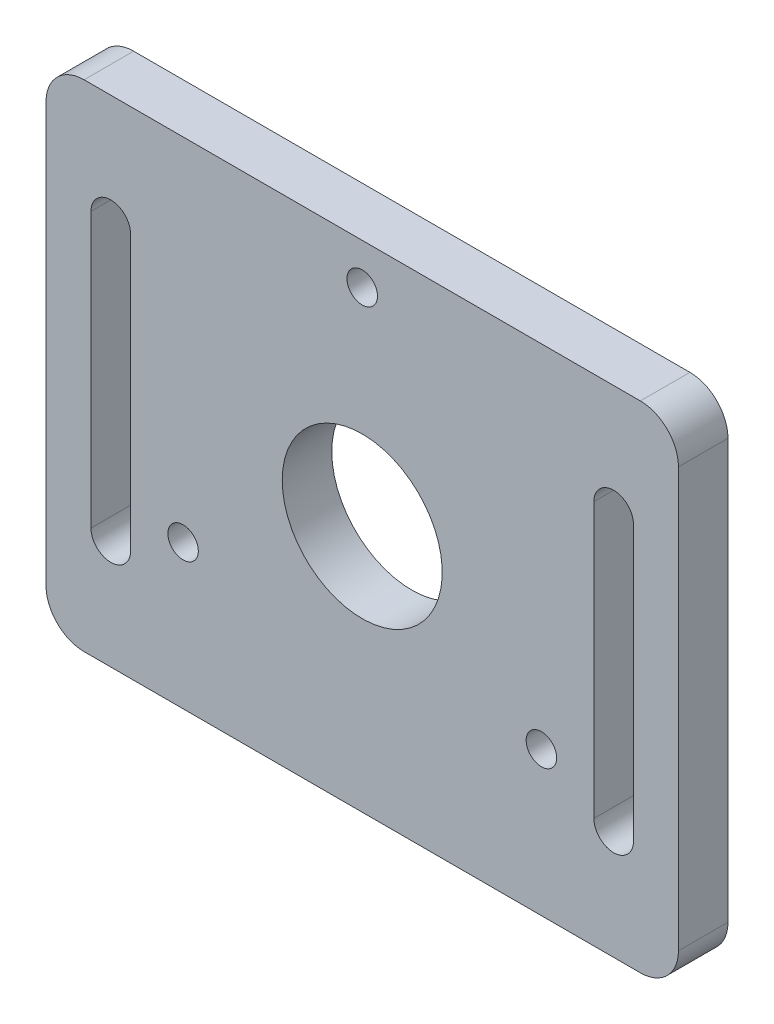
SolidWorks part; units mm, degrees
material "AISI 316 Annealed Stainless Steel Bar (SS)"
ref_plane "Front Plane" through (0, 0, 0) normal (0, 0, 1) x (1, 0, 0)
ref_plane "Top Plane" through (0, 0, 0) normal (0, 1, 0) x (1, 0, 0)
ref_plane "Right Plane" through (0, 0, 0) normal (1, 0, 0) x (0, 0, -1)
sketch "Sketch1" plane through (0, 0, 0) normal (0, 0, 1) x (1, 0, 0)
  line L0 (33, -18) -> (33, 18) construction
  line L1 (-41.5, -32.5) -> (41.5, -32.5)
  line L2 (-41.5, -32.5) -> (-41.5, 32.5)
  line L3 (-41.5, 32.5) -> (41.5, 32.5)
  line L4 (41.5, -32.5) -> (41.5, 32.5)
  line L15 (30.4, -18) -> (30.4, 18)
  line L16 (35.6, -18) -> (35.6, 18)
  line L18 (-33, -18) -> (-33, 18) construction
  line L19 (-30.4, -18) -> (-30.4, 18)
  line L20 (-35.6, -18) -> (-35.6, 18)
  circle A0 centre (0, 0) radius 10.5
  arc A9 (30.4, -18) -> (35.6, -18) centre (33, -18) ccw
  arc A10 (35.6, 18) -> (30.4, 18) centre (33, 18) ccw
  arc A11 (-30.4, -18) -> (-35.6, -18) centre (-33, -18) cw
  arc A12 (-35.6, 18) -> (-30.4, 18) centre (-33, 18) cw
  point P0 (0, 0)
  point P8 (0, 32.5)
  point P12 (33, -2.35)
  point P15 (33, 0)
  point P19 (0, 0)
  point P24 (-33, 0)
  point P27 (-24.387, -2.35)
  dimension "D3" = 21
  dimension "D4" = 33
  dimension "D9" = 32.5
  dimension "D1" = 83
  dimension "D2" = 65
  dimension "D6" = 33
  dimension "D7" = 18
  dimension "D10" = 66
  dimension "D5" = 5.2
extrude "Boss-Extrude1" add sketch "Sketch1" along normal blind 6.5
fillet "Fillet1" radius 5 4 edges at (41.5, -32.5, 3.25) (-41.5, -32.5, 3.25) (-41.5, 32.5, 3.25) (41.5, 32.5, 3.25)
sketch "Sketch2" plane through (0, 0, 6.5) normal (0, 0, 1) x (1, 0, 0)
  circle A0 centre (0, 27.15) radius 2
  circle A1 centre (23.5126, -13.575) radius 2
  circle A2 centre (-23.5126, -13.575) radius 2
  circle A3 centre (0, 0) radius 27.15 construction
  dimension "D1" = 4
  dimension "D2" = 27.15
  dimension "D3" = 3
extrude "Cut-Extrude1" cut sketch "Sketch2" against normal blind 10
